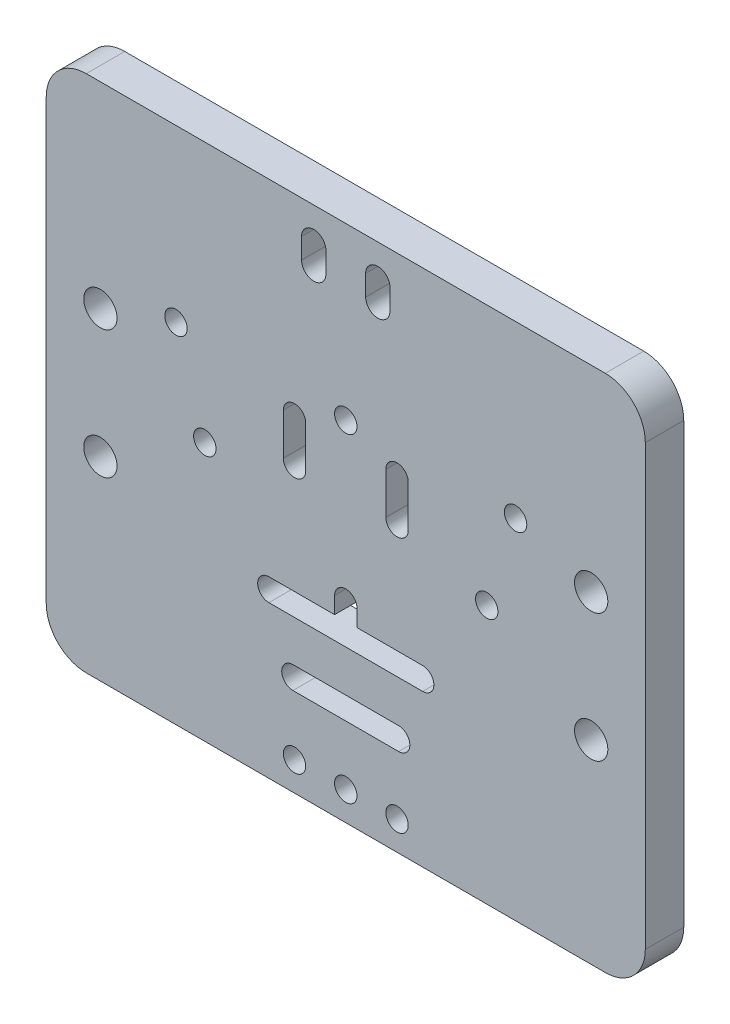
SolidWorks part; units mm, degrees
material "Polycarbonate (PC)"
ref_plane "Спереди" through (0, 0, 0) normal (0, 0, 1) x (1, 0, 0)
ref_plane "Сверху" through (0, 0, 0) normal (0, 1, 0) x (1, 0, 0)
ref_plane "Справа" through (0, 0, 0) normal (1, 0, 0) x (0, 0, -1)
sketch "Model" plane through (0, 0, 0) normal (0, 0, 1) x (1, 0, 0)
  line L0 (0, 0) -> (0, 91.7343) construction
  line L1 (5, 79.6063) -> (5, 68.5159) construction
  line L2 (-2.3648, 54.4) -> (2.3481, 54.4) construction
  line L3 (8, 54.1038) -> (8, 41.41) construction
  line L6 (-17.4644, 25.5) -> (15.7269, 25.5) construction
  line L15 (26.5, 56.989) -> (26.5, 51.9054) construction
  line L16 (23.9154, 54.4) -> (29.241, 54.4) construction
  line L17 (22, 42.5983) -> (22, 38.5529) construction
  line L18 (19.8952, 40.4) -> (24.0146, 40.4) construction
  line L19 (-5, 79.6063) -> (-5, 68.5159) construction
  line L20 (-3.1, 75.8) -> (-3.1, 72.6)
  line L21 (-6.9, 72.6) -> (-6.9, 75.8)
  line L22 (-6.9, 75.8) -> (-6.9, 72.6)
  line L23 (-3.1, 72.6) -> (-3.1, 75.8)
  line L33 (-19.8952, 40.4) -> (-24.0146, 40.4) construction
  line L34 (-22, 42.5983) -> (-22, 38.5529) construction
  line L35 (-23.9154, 54.4) -> (-29.241, 54.4) construction
  line L36 (-26.5, 56.989) -> (-26.5, 51.9054) construction
  line L37 (-8, 54.1038) -> (-8, 41.41) construction
  line L38 (-9.75, 50.9) -> (-9.75, 44.4)
  line L39 (-6.25, 44.4) -> (-6.25, 50.9)
  line L40 (-6.25, 50.9) -> (-6.25, 44.4)
  line L41 (-9.75, 44.4) -> (-9.75, 50.9)
  line L42 (-8.25, 15.5) -> (8.25, 15.5) construction
  line L1661 (3.1, 72.6) -> (3.1, 75.8)
  line L1674 (6.9, 75.8) -> (6.9, 72.6)
  line L1730 (46.75, 74.75) -> (46.75, 6.25)
  line L1743 (40.5, 0) -> (-40.5, 0)
  line L1756 (-46.75, 6.25) -> (-46.75, 74.75)
  line L1769 (-40.5, 81) -> (40.5, 81)
  line L1807 (8.25, 17.25) -> (-8.25, 17.25)
  line L1820 (-8.25, 13.75) -> (8.25, 13.75)
  line L2052 (6.9, 72.6) -> (6.9, 75.8)
  line L2065 (3.1, 75.8) -> (3.1, 72.6)
  line L2109 (9.75, 44.4) -> (9.75, 50.9)
  line L2122 (6.25, 50.9) -> (6.25, 44.4)
  line L2254 (-1.75, 29.85) -> (-1.75, 27.25)
  line L2255 (-1.75, 27.25) -> (-12, 27.25)
  line L2268 (-12, 23.75) -> (12, 23.75)
  line L2281 (12, 27.25) -> (1.75, 27.25)
  line L2282 (1.75, 27.25) -> (1.75, 29.85)
  line L2413 (6.25, 44.4) -> (6.25, 50.9)
  line L2426 (9.75, 50.9) -> (9.75, 44.4)
  line L2519 (8.25, 13.75) -> (-8.25, 13.75)
  line L2532 (-8.25, 17.25) -> (8.25, 17.25)
  line L2808 (1.75, 29.85) -> (1.75, 27.25)
  line L2809 (1.75, 27.25) -> (12, 27.25)
  line L2822 (12, 23.75) -> (-12, 23.75)
  line L2835 (-12, 27.25) -> (-1.75, 27.25)
  line L2836 (-1.75, 27.25) -> (-1.75, 29.85)
  arc A0 (-46.75, 74.75) -> (-40.5, 81) centre (-40.5, 74.75) cw
  arc A1 (40.5, 81) -> (46.75, 74.75) centre (40.5, 74.75) cw
  arc A2 (46.75, 6.25) -> (40.5, 0) centre (40.5, 6.25) cw
  arc A3 (-46.75, 6.25) -> (-40.5, 0) centre (-40.5, 6.25) ccw
  arc A4 (6.9, 75.8) -> (3.1, 75.8) centre (5, 75.8) ccw
  arc A5 (3.1, 72.6) -> (6.9, 72.6) centre (5, 72.6) ccw
  circle A7 centre (0, 4.5) radius 1.75
  circle A8 centre (8, 4.5) radius 1.75
  arc A11 (-8.25, 17.25) -> (-8.25, 13.75) centre (-8.25, 15.5) ccw
  arc A12 (8.25, 13.75) -> (8.25, 17.25) centre (8.25, 15.5) ccw
  arc A13 (1.75, 29.85) -> (-1.75, 29.85) centre (0, 29.85) ccw
  arc A14 (12, 23.75) -> (12, 27.25) centre (12, 25.5) ccw
  arc A15 (-12, 23.75) -> (-12, 27.25) centre (-12, 25.5) cw
  arc A18 (-3.1, 72.6) -> (-6.9, 72.6) centre (-5, 72.6) cw
  arc A19 (-6.9, 75.8) -> (-3.1, 75.8) centre (-5, 75.8) cw
  circle A22 centre (-8, 4.5) radius 1.75
  circle A26 centre (0, 54.4) radius 1.75
  circle A27 centre (26.5, 54.4) radius 1.75
  circle A28 centre (22, 40.4) radius 1.75
  arc A29 (9.75, 50.9) -> (6.25, 50.9) centre (8, 50.9) ccw
  arc A30 (9.75, 44.4) -> (6.25, 44.4) centre (8, 44.4) cw
  circle A31 centre (-22, 40.4) radius 1.75
  circle A32 centre (-26.5, 54.4) radius 1.75
  arc A33 (-9.75, 44.4) -> (-6.25, 44.4) centre (-8, 44.4) ccw
  arc A34 (-9.75, 50.9) -> (-6.25, 50.9) centre (-8, 50.9) cw
other "AlignGroup2" parameters "D1"=6.25, "D7"=1.9219, "D9"=1.9, "D15"=4.2806, "D16"=4.3202, "D17"=3.6469, "D18"=3.4163, "D19"=2.8765, "D27"=1.8346, "D28"=1.7517, "D30"=1.7966, "D31"=1.8139, "D32"=1.7917, "D41"=5.3359, "D42"=5.9697, "D43"=2.215, "D44"=4.745, "D45"=3.825, "D49"=1.5281, "D50"=1.5028, "D2"=81.39, "D3"=81, "D4"=91.7343, "D5"=3.2143, "D6"=3.2, "D8"=5.1441, "D10"=91.7343, "D11"=5.2463, "D12"=91.7343, "D13"=4.9184, "D14"=3, "D20"=29.739, "D21"=23.9282, "D22"=2.6, "D23"=2.6, "D24"=10.3, "D25"=16.5262, "D26"=0.431, "D29"=24, "D33"=91.7343, "D34"=91.7343, "D35"=91.7343, "D36"=91.7343, "D37"=7.9346, "D38"=7.2498, "D39"=4.713, "D40"=81, "D46"=6.5, "D47"=6.5, "D48"=4.713
extrude "Base" add sketch "Model" along normal blind 6
hole_wizard "Ø5.2 (5.2) Diameter Hole1" positions "Sketch1" profile "Sketch2" hole size "Ø5.2" standard "ANSI Metric" end condition through all
sketch "Sketch1" plane through (0, 0, 6) normal (0, 0, 1) x (1, 0, 0)
  line L0 (40.5, 0) -> (-40.5, 0) construction
  line L1 (0, 0) -> (0, 27.996) construction
  point P0 (-38.3, 50.35)
  point P2 (-38.3, 30.35)
  point P6 (38.3, 30.35)
  point P8 (38.3, 50.35)
  point P22 (0, 0)
  dimension "D1" = 20
  dimension "D2" = 30.35
  dimension "D3" = 76.6
sketch "Sketch2" plane through (-38.3, 50.35, 6) normal (1, 0, 0) x (0, -1, 0)
  line L0 (0, 0) -> (0, 6)
  line L1 (0, 6) -> (2.6, 6)
  line L2 (2.6, 6) -> (2.6, 0)
  line L5 (2.6, 0) -> (0, 0)
  line L11 (0, -6.35) -> (0, 107.95) construction
  dimension "Thru Hole Dia." = 5.2
  dimension "Thru Hole Depth" = 6
